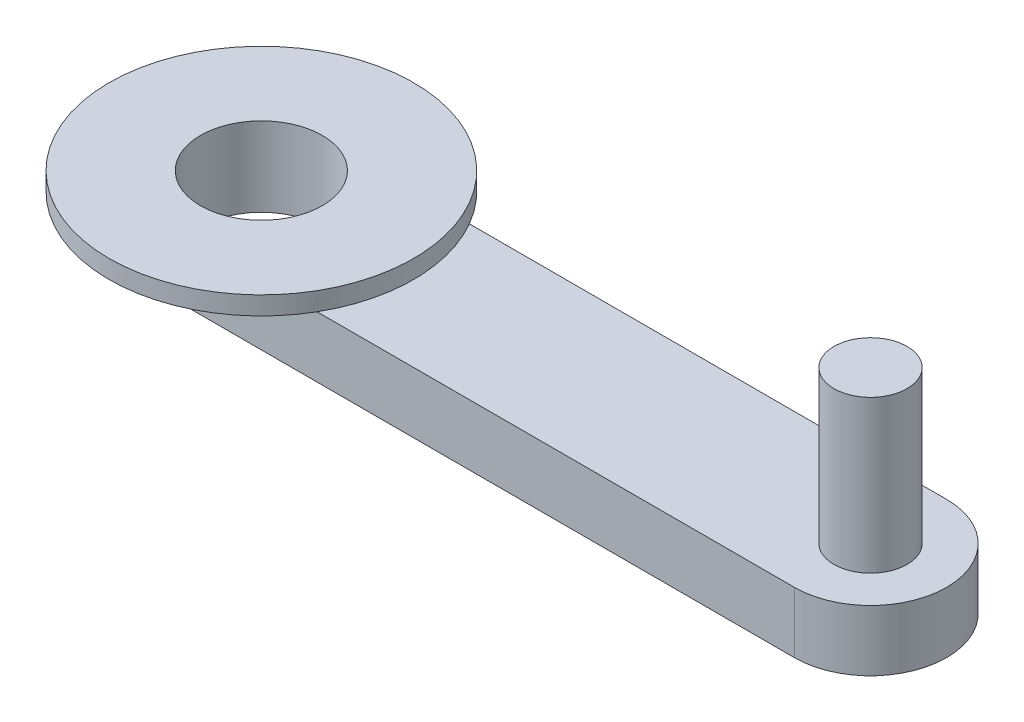
SolidWorks part; units mm, degrees
ref_plane "Front Plane" through (0, 0, 0) normal (0, 0, 1) x (1, 0, 0)
ref_plane "Top Plane" through (0, 0, 0) normal (0, 1, 0) x (1, 0, 0)
ref_plane "Right Plane" through (0, 0, 0) normal (1, 0, 0) x (0, 0, -1)
sketch "Sketch1" plane through (0, 0, 0) normal (0, 1, 0) x (1, 0, 0)
  line L0 (0, 0) -> (-25.4, 0) construction
  line L1 (0, -3.175) -> (-25.4, -3.175)
  line L2 (0, 3.175) -> (-25.4, 3.175)
  arc A0 (0, -3.175) -> (0, 3.175) centre (0, 0) ccw
  arc A1 (-25.4, 3.175) -> (-25.4, -3.175) centre (-25.4, 0) ccw
  point P3 (-12.7, 0)
  dimension "D2" = 3.175
  dimension "D1" = 25.4
extrude "Boss-Extrude1" add sketch "Sketch1" along normal blind 2.54
sketch "Sketch2" plane through (0, 2.54, 0) normal (0, 1, 0) x (1, 0, 0)
  circle A0 centre (0, 0) radius 1.524
  dimension "D1" = 3.048
extrude "Boss-Extrude2" add sketch "Sketch2" along normal blind 6.35
sketch "Sketch3" plane through (0, 2.54, 0) normal (0, 1, 0) x (1, 0, 0)
  circle A0 centre (-25.4, 0) radius 2.54
  arc A1 (-25.4, 3.175) -> (-25.4, -3.175) centre (-25.4, 0) ccw construction
  dimension "D1" = 5.08
extrude "Cut-Extrude1" cut sketch "Sketch3" against normal through all
sketch "Sketch4" plane through (0, 2.54, 0) normal (0, 1, 0) x (1, 0, 0)
  circle A1 centre (-25.4, 0) radius 2.54
  circle A3 centre (-25.4, 0) radius 2.54 construction
  circle A4 centre (-25.4, 0) radius 6.35
  dimension "D1" = 12.7
extrude "Boss-Extrude3" add sketch "Sketch4" along normal blind 0.762
